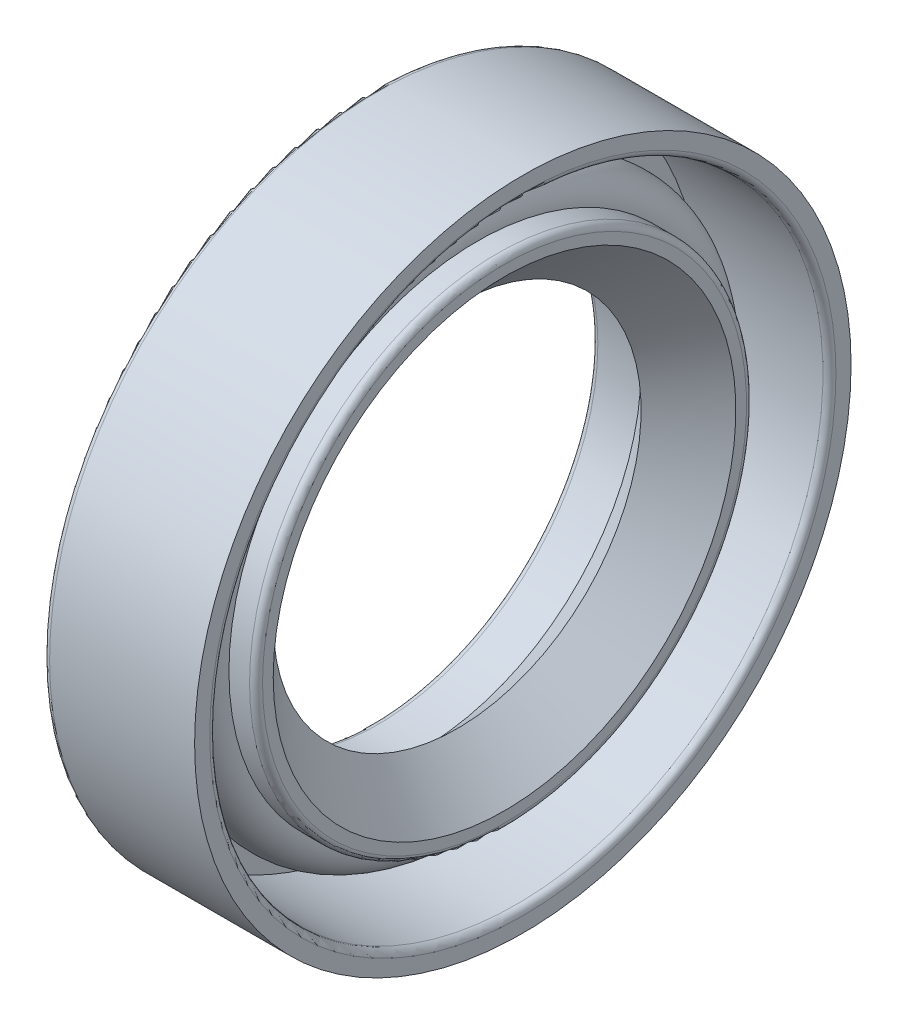
SolidWorks part; units mm, degrees
ref_plane "Ön Düzlem" through (0, 0, 0) normal (0, 0, 1) x (1, 0, 0)
ref_plane "Üst Düzlem" through (0, 0, 0) normal (0, 1, 0) x (1, 0, 0)
ref_plane "Sağ Düzlem" through (0, 0, 0) normal (1, 0, 0) x (0, 0, -1)
sketch "Çizim1" plane through (0, 0, 0) normal (0, 0, 1) x (1, 0, 0)
  line L0 (0, 0) -> (0, 15.1672) construction
  line L1 (0, 0) -> (7.802, 0) construction
  line L2 (7, 15.1672) -> (0.3, 15.1672)
  line L3 (0, 14.8672) -> (0, 10.4672)
  line L4 (0.3, 10.1672) -> (2.2976, 10.1672)
  line L5 (2.2976, 10.1672) -> (3.9647, 8.5)
  line L6 (6.154, 10.6892) -> (6.154, 11.1826)
  line L7 (5.854, 11.4826) -> (4.9018, 11.4826)
  line L8 (3.9647, 8.5) -> (6.154, 10.6892)
  line L9 (2.2976, 11.6672) -> (1, 11.6672)
  line L10 (1, 11.6672) -> (1, 14.1672)
  line L11 (1, 14.1672) -> (6.7, 14.1672)
  line L12 (7, 14.4672) -> (7, 15.1672)
  arc A0 (4.9018, 11.4826) -> (2.2976, 11.6672) centre (3.5997, 11.5749) ccw
  arc A1 (5.854, 11.4826) -> (6.154, 11.1826) centre (5.854, 11.1826) cw
  arc A2 (0, 10.4672) -> (0.3, 10.1672) centre (0.3, 10.4672) ccw
  arc A3 (7, 14.4672) -> (6.7, 14.1672) centre (6.7, 14.4672) cw
  arc A4 (0, 14.8672) -> (0.3, 15.1672) centre (0.3, 14.8672) cw
  point P8 (0, 0)
  point P17 (0, 0)
  point P22 (0, 10.1672)
  point P28 (0, 0)
  point P29 (4.5818, 11.6337)
  point P30 (4.9018, 11.4826)
  dimension "D7" = 0.3
  dimension "D1" = 7
  dimension "D2" = 1
  dimension "D3" = 1
  dimension "D4" = 2.5
  dimension "D5" = 5
  dimension "D6" = 8.5
revolve "Döndür1" add sketch "Çizim1" angle 360 about L1
